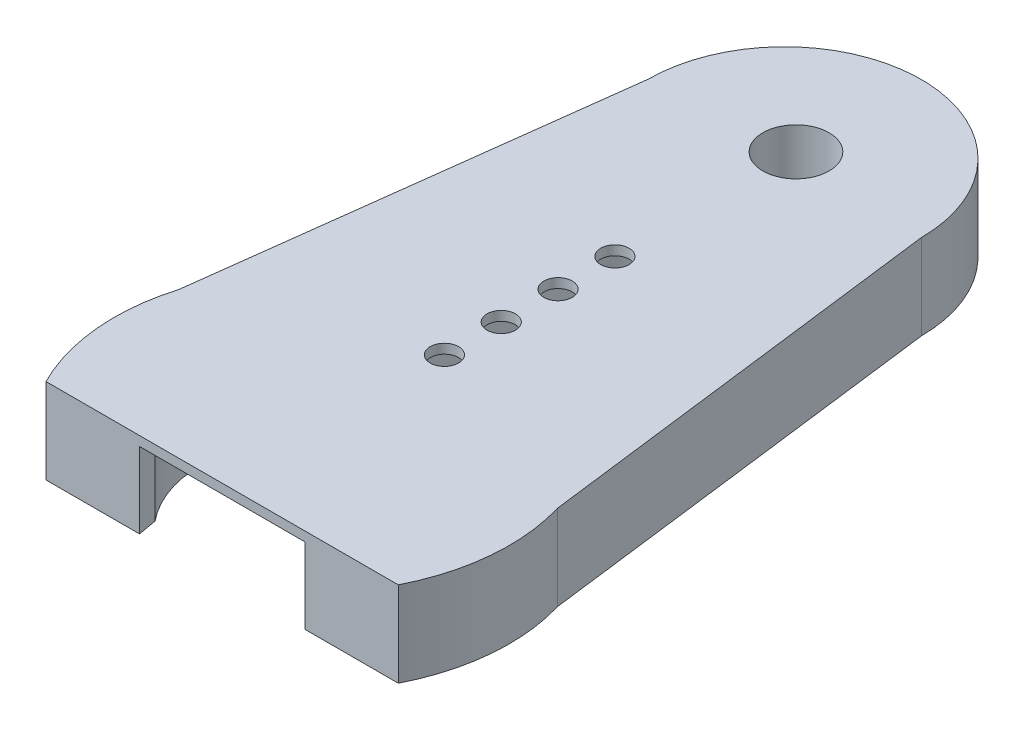
SolidWorks part; units mm, degrees
ref_plane "Płaszczyzna przednia" through (0, 0, 0) normal (0, 0, 1) x (1, 0, 0)
ref_plane "Płaszczyzna górna" through (0, 0, 0) normal (0, 1, 0) x (1, 0, 0)
ref_plane "Płaszczyzna prawa" through (0, 0, 0) normal (1, 0, 0) x (0, 0, -1)
sketch "Szkic1" plane through (0, 0, 0) normal (0, 1, 0) x (1, 0, 0)
  line L0 (0, 24.9587) -> (0, 32.1838) construction
  line L2 (-5.0678, 2.9721) -> (-3.0037, 14.821)
  line L3 (5.0678, 2.9721) -> (2.9625, 14.821)
  line L4 (0, 0) -> (0, 19.99) construction
  line L5 (0, 0) -> (0, -5.875) construction
  line L7 (-5.0678, 2.9721) -> (-9.9984, 2.9721) construction
  line L8 (-9.9984, 2.9721) -> (9.9984, 2.9721) construction
  line L9 (-7.2251, 24.9721) -> (-9.9984, 2.9721)
  line L10 (7.2251, 24.9721) -> (9.9984, 2.9721)
  arc A0 (-5.0678, 2.9721) -> (5.0678, 2.9721) centre (0, 0) ccw
  arc A1 (-2.8928, 16.9965) -> (2.8928, 16.9965) centre (0, 17.0955) cw
  arc A3 (-7.2251, 24.9721) -> (7.2251, 24.9721) centre (0, 24.9587) cw
  arc A4 (-9.9984, 2.9721) -> (9.9984, 2.9721) centre (0, 0) ccw
  spline S0 degree 1 poles (-2.8928, 16.9965) (-3.0037, 14.821) knots 0 0 1 1
  spline S1 degree 1 poles (2.8928, 16.9965) (2.9625, 14.821) knots 0 0 1 1
  point P18 (0, -19)
  dimension "D1" = 11.75
  dimension "D6" = 22
  dimension "D4" = 7.2251
  dimension "D5" = 22
  dimension "D8" = 14.4502
extrude "Dodanie-wyciągnięcie1" add sketch "Szkic1" along normal blind 4
sketch "Szkic2" plane through (0, 4, 0) normal (0, 1, 0) x (1, 0, 0)
  line L0 (-7.2251, 24.9721) -> (-9.9984, 2.9721)
  line L1 (7.2251, 24.9721) -> (9.9984, 2.9721)
  arc A0 (-7.2251, 24.9721) -> (7.2251, 24.9721) centre (0, 24.9587) cw
  arc A2 (-9.9984, 2.9721) -> (9.9984, 2.9721) centre (0, 0) ccw
extrude "Dodanie-wyciągnięcie2" add sketch "Szkic2" along normal blind 0.5
sketch "Szkic5" plane through (0, 0, 0) normal (0, -1, 0) x (1, 0, 0)
  line L5 (-2.2124, 17.0955) -> (2.2376, 17.0955)
  line L6 (-4.5333, 3.7369) -> (-2.2124, 17.0955)
  line L7 (2.2376, 17.0955) -> (4.5344, 3.7356)
  arc A0 (5.0678, -2.9721) -> (-5.0678, -2.9721) centre (0, 0) ccw construction
  arc A1 (5.0678, -2.9721) -> (-5.0678, -2.9721) centre (0, 0) ccw construction
  arc A3 (-4.5333, 3.7369) -> (4.5344, 3.7356) centre (0, 0) cw
  point P17 (0.0126, 17.0955)
  dimension "D2" = 4.45
extrude "Wytnij-wyciągnięcie6" cut sketch "Szkic5" against normal blind 4
sketch "Szkic7" plane through (0, 0, 0) normal (0, -1, 0) x (1, 0, 0)
  line L0 (-9.2942, 4.7349) -> (9.2973, 4.7288)
  arc A0 (-3.4737, 9.8354) -> (-9.9984, -2.9721) centre (0, 0) ccw construction
  arc A1 (9.9984, -2.9721) -> (3.4865, 9.8309) centre (0, 0) ccw construction
  arc A2 (-9.2942, 4.7349) -> (9.2973, 4.7288) centre (0, 0) cw
extrude "Wytnij-wyciągnięcie7" cut sketch "Szkic7" against normal blind 10
sketch "Szkic8" plane through (0, 0, 0) normal (0, -1, 0) x (1, 0, 0)
  line L0 (0, -32.1838) -> (0, -25.5638) construction
  arc A0 (-7.2251, -24.9721) -> (7.2251, -24.9721) centre (0, -24.9587) ccw construction
  circle A1 centre (0, -25.5638) radius 1.75
  dimension "D2" = 3.5
  dimension "D1" = 6.62
extrude "Wytnij-wyciągnięcie8" cut sketch "Szkic8" against normal blind 10
sketch "Szkic9" plane through (0, 4, 0) normal (0, -1, 0) x (1, 0, 0)
  line L0 (0, -32.1838) -> (0, -16.0038) construction
  line L1 (0, -16.0038) -> (0, -13.0038) construction
  line L2 (0, -13.0038) -> (0, -10.0038) construction
  line L3 (0, -10.0038) -> (0, -7.0038) construction
  arc A0 (-7.2251, -24.9721) -> (7.2251, -24.9721) centre (0, -24.9587) ccw construction
  circle A1 centre (0, -16.0038) radius 0.75
  circle A2 centre (0, -13.0038) radius 0.75
  circle A3 centre (0, -10.0038) radius 0.75
  circle A4 centre (0, -7.0038) radius 0.75
  dimension "D2" = 1.5
  dimension "D4" = 1.5
  dimension "D6" = 1.5
  dimension "D8" = 1.5
  dimension "D1" = 16.18
  dimension "D3" = 3
  dimension "D5" = 3
  dimension "D7" = 3
extrude "Wytnij-wyciągnięcie9" cut sketch "Szkic9" against normal blind 10
